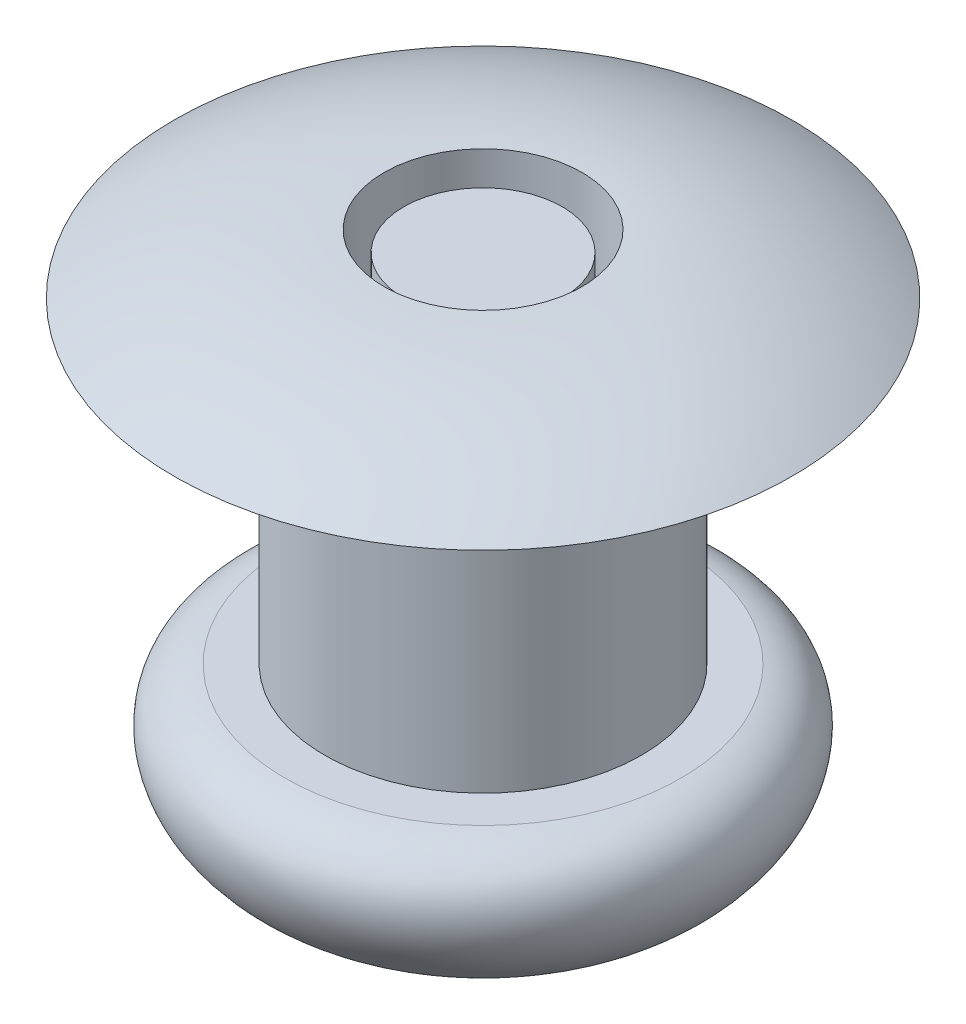
SolidWorks part; units mm, degrees
material "AISI 316 Arkusz stali nierdzewnej (SS)"
ref_plane "Płaszczyzna przednia" through (0, 0, 0) normal (0, 0, 1) x (1, 0, 0)
ref_plane "Płaszczyzna górna" through (0, 0, 0) normal (0, 1, 0) x (1, 0, 0)
ref_plane "Płaszczyzna prawa" through (0, 0, 0) normal (1, 0, 0) x (0, 0, -1)
sketch "Szkic1" plane through (0, 0, 0) normal (0, 0, 1) x (1, 0, 0)
  line L0 (0, 0) -> (0, 0.724) construction
  line L1 (-3.9, 0) -> (-2, 0)
  line L2 (-1.25, 0.75) -> (-1.25, -4)
  line L3 (-2, 0) -> (-2, -4)
  line L4 (-1.25, -4) -> (-1, -4)
  line L5 (-1, -4) -> (-1, 0.5)
  line L6 (-1, 0.5) -> (0, 0.5)
  line L7 (-2, -4) -> (-2.5, -4)
  line L8 (0, 0) -> (0, -5.4215) construction
  line L9 (0, 0.5) -> (0, -5.4215) construction
  line L10 (0, 0.5) -> (0, -5.4215)
  line L15 (6.75, -4) -> (-15.25, -4) construction
  arc A0 (-1.25, 0.75) -> (-3.9, 0) centre (-1.25, -4.3067) ccw
  spline S0 degree 3 poles (-2.5, -4) (-3.3276, -4.1478) (-3.2549, -5.9654) (-0.0301, -6.3768) (-1.229, -4.325) (-0.2169, -5.4912) (0, -5.4215) knots 0 0 0 0 0.343812 0.687239 0.819799 1 1 1 1
  dimension "D1" = 7.8
  dimension "D2" = 0.75
  dimension "D3" = 4
  dimension "D4" = 2.5
  dimension "D5" = 0.5
  dimension "D6" = 2
  dimension "D7" = 5
  dimension "D8" = 1.5978
  dimension "D9" = 0.3519
  dimension "D10" = 1.5835
  dimension "D11" = 1.2582
  dimension "D12" = 1.4215
  dimension "D13" = 0.8591
  dimension "D14" = 0.7171
  dimension "D15" = 1.256
  dimension "D16" = 1.715
  dimension "D17" = 5.1929
  dimension "D18" = 6.0862
revolve "Obrót1" add sketch "Szkic1" angle 360 about L9
